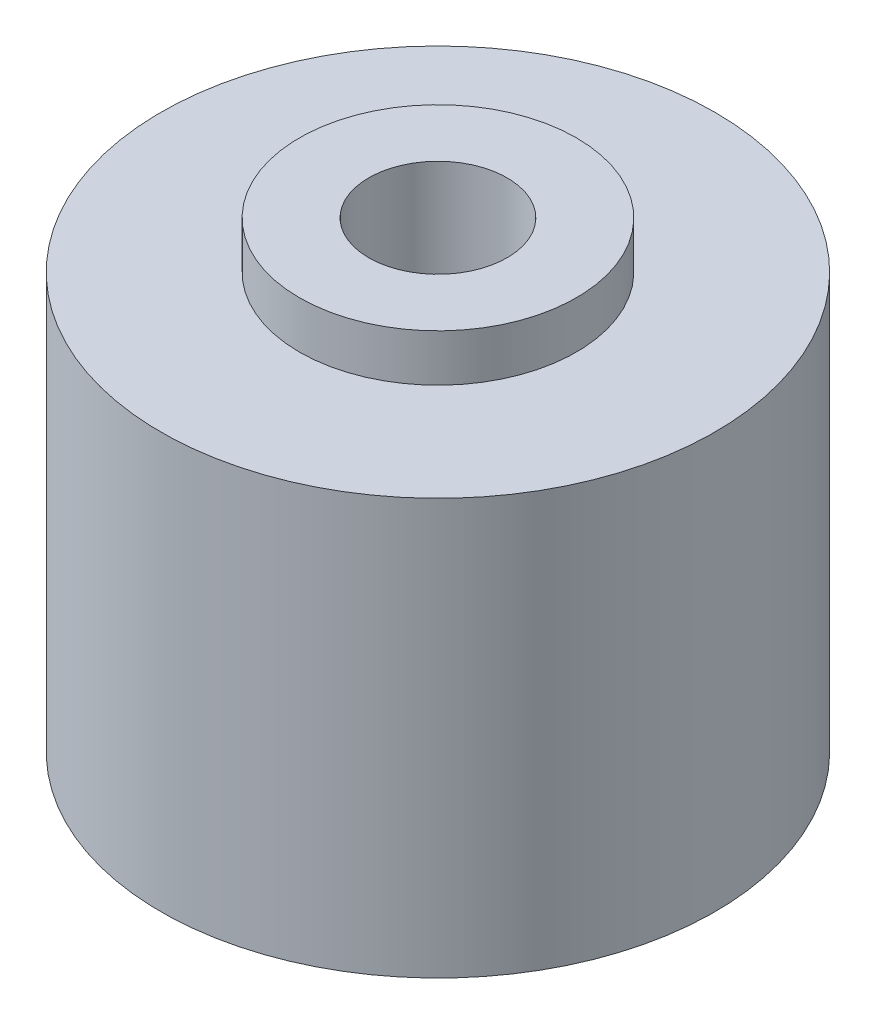
SolidWorks part; units mm, degrees
ref_plane "Front Plane" through (0, 0, 0) normal (0, 0, 1) x (1, 0, 0)
ref_plane "Top Plane" through (0, 0, 0) normal (0, 1, 0) x (1, 0, 0)
ref_plane "Right Plane" through (0, 0, 0) normal (1, 0, 0) x (0, 0, -1)
sketch "Sketch1" plane through (0, 0, 0) normal (0, 1, 0) x (1, 0, 0)
  circle A0 centre (0, 0) radius 12.7
  dimension "D1" = 25.4
extrude "Boss-Extrude1" add sketch "Sketch1" along normal blind 19.05
sketch "Sketch2" plane through (0, 19.05, 0) normal (0, 1, 0) x (1, 0, 0)
  circle A0 centre (0, 0) radius 6.35
  dimension "D1" = 12.7
extrude "Boss-Extrude2" add sketch "Sketch2" along normal blind 2.159
sketch "Sketch4" plane through (0, 21.209, 0) normal (0, 1, 0) x (1, 0, 0)
  circle A2 centre (0, 0) radius 3.175
  dimension "D1" = 6.35
extrude "Cut-Extrude4" cut sketch "Sketch4" against normal through all
